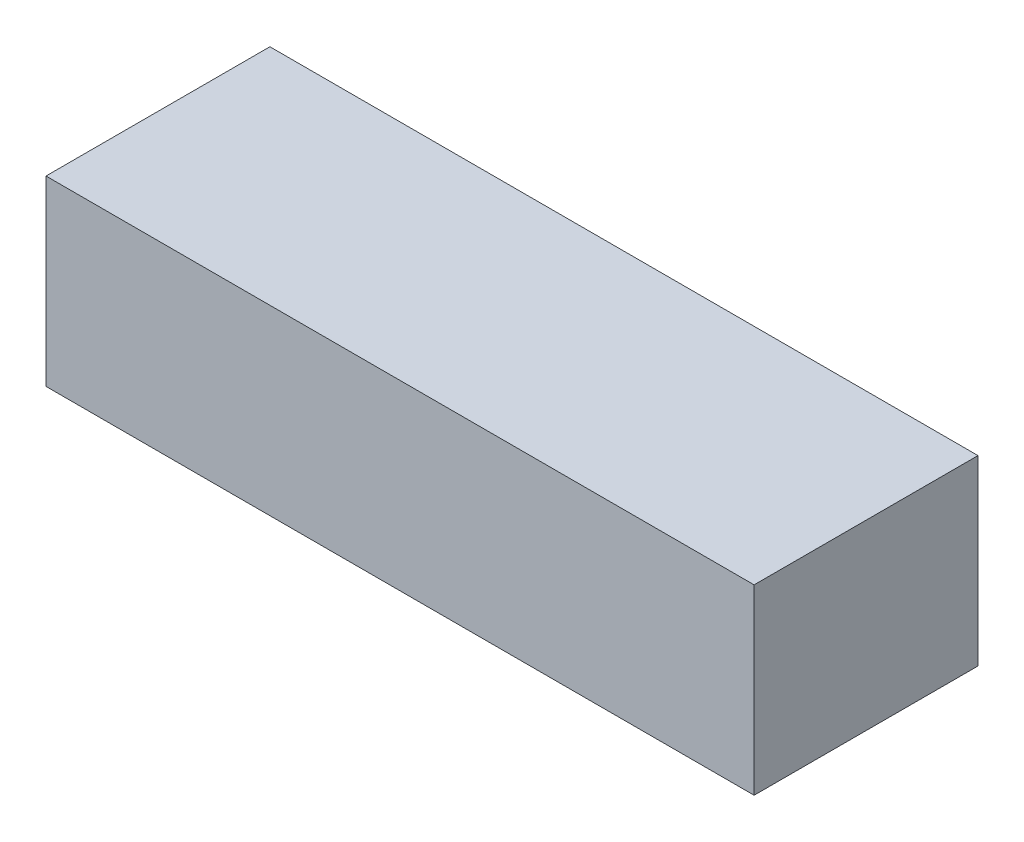
SolidWorks part; units mm, degrees
ref_plane "Front Plane" through (0, 0, 0) normal (0, 0, 1) x (1, 0, 0)
ref_plane "Top Plane" through (0, 0, 0) normal (0, 1, 0) x (1, 0, 0)
ref_plane "Right Plane" through (0, 0, 0) normal (1, 0, 0) x (0, 0, -1)
sketch "Sketch1" plane through (0, 0, 0) normal (0, 1, 0) x (1, 0, 0)
  line L1 (-68, 21.5) -> (68, 21.5)
  line L2 (-68, 21.5) -> (-68, -21.5)
  line L3 (-68, -21.5) -> (68, -21.5)
  line L4 (68, 21.5) -> (68, -21.5)
  line L5 (-68, 21.5) -> (68, -21.5) construction
  line L6 (-68, -21.5) -> (68, 21.5) construction
  point P0 (0, 0)
  dimension "D1" = 136
  dimension "D2" = 43
extrude "Boss-Extrude1" add sketch "Sketch1" along normal blind 35
